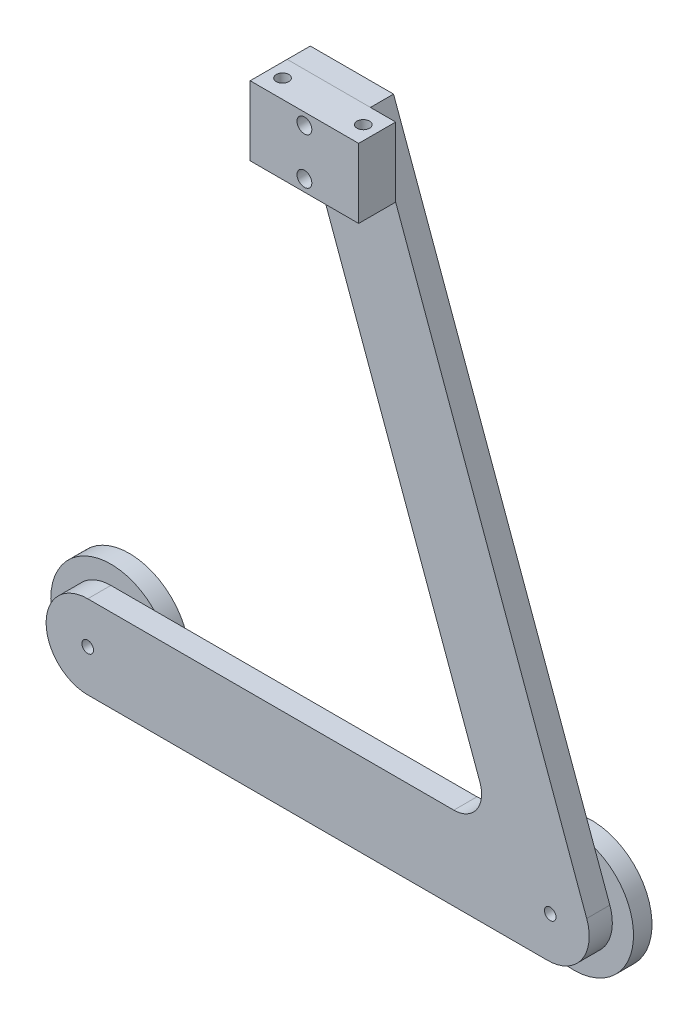
SolidWorks part; units mm, degrees
material "ﾊﾞﾙｻ"
ref_plane "正面" through (0, 0, 0) normal (0, 0, 1) x (1, 0, 0)
ref_plane "平面" through (0, 0, 0) normal (0, 1, 0) x (1, 0, 0)
ref_plane "右側面" through (0, 0, 0) normal (1, 0, 0) x (0, 0, -1)
sketch "ｽｹｯﾁ1" plane through (0, 0, 0) normal (0, 0, 1) x (1, 0, 0)
  line L0 (-44.6071, 122.557) -> (-2.9307, 8.0521)
  line L1 (-8.5689, 0) -> (-87.7243, 0)
  line L3 (-87.7243, -18) -> (11.6981, -18)
  line L4 (20.1554, -5.9218) -> (-26.6071, 122.557)
  line L5 (-26.6071, 122.557) -> (-44.6071, 122.557)
  line L6 (-87.7243, -9) -> (12.2757, -9) construction
  line L7 (12.2757, -9) -> (-35.6071, 122.557) construction
  arc A0 (11.6981, -18) -> (20.1554, -5.9218) centre (11.6981, -9) ccw
  arc A1 (-96.7243, -9) -> (-87.7243, -18) centre (-87.7243, -9) ccw
  arc A2 (-87.7243, 0) -> (-96.7243, -9) centre (-87.7243, -9) ccw
  circle A3 centre (12.2757, -9) radius 1.25
  circle A4 centre (-87.7243, -9) radius 1.25
  arc A5 (-2.9307, 8.0521) -> (-8.5689, 0) centre (-8.5689, 6) cw
  point P14 (-87.7243, -18)
  point P17 (-87.7243, 0)
  point P20 (0, 0)
  dimension "D1" = 6
  dimension "D6" = 2.5
  dimension "D2" = 140
  dimension "D3" = 100
  dimension "D4" = 18
  dimension "D5" = 18
  dimension "D7" = 70
extrude "ﾎﾞｽ - 押し出し1" add sketch "ｽｹｯﾁ1" along normal blind 5
sketch "ｽｹｯﾁ2" plane through (0, 0, 5) normal (0, 0, 1) x (1, 0, 0)
  line L0 (20.1554, -5.9218) -> (-26.6071, 122.557) construction
  line L1 (-44.6071, 122.557) -> (-21.1475, 122.557)
  line L2 (-44.6071, 122.557) -> (-44.6071, 107.557)
  line L3 (-44.6071, 107.557) -> (-21.1475, 107.557)
  line L4 (-21.1475, 122.557) -> (-21.1475, 107.557)
  line L5 (-44.6071, 115.057) -> (-21.1475, 115.057) construction
  line L7 (-32.8773, 122.557) -> (-32.8773, 107.557) construction
  dimension "D1" = 15
extrude "ﾎﾞｽ - 押し出し2" add sketch "ｽｹｯﾁ2" along normal blind 8 separate body
sketch "ｽｹｯﾁ3" plane through (0, 0, 13) normal (0, 0, 1) x (1, 0, 0)
  line L0 (-44.6071, 115.057) -> (-21.1475, 115.057) construction
  line L1 (-44.6071, 122.557) -> (-44.6071, 107.557) construction
  line L2 (-21.1475, 107.557) -> (-21.1475, 122.557) construction
  line L4 (-21.1475, 122.557) -> (-44.6071, 122.557) construction
  line L5 (-32.8773, 122.557) -> (-32.8773, 115.057) construction
  circle A0 centre (-32.8773, 120.057) radius 1.6
  circle A1 centre (-32.8773, 110.057) radius 1.6
  dimension "D1" = 3.2
  dimension "D2" = 10
extrude "ｶｯﾄ - 押し出し1" cut sketch "ｽｹｯﾁ3" against normal through all
sketch "ｽｹｯﾁ4" plane through (0, 107.557, 0) normal (0, -1, 0) x (1, 0, 0)
  line L0 (-21.1475, 9) -> (-44.6071, 9) construction
  line L1 (-21.1475, 13) -> (-21.1475, 5) construction
  line L2 (-44.6071, 13) -> (-44.6071, 5) construction
  line L4 (-44.6071, 13) -> (-21.1475, 13) construction
  line L5 (-32.8773, 13) -> (-32.8773, 5) construction
  line L6 (-44.6071, 5) -> (-21.1475, 5) construction
  circle A0 centre (-24.1475, 9) radius 1.35
  circle A1 centre (-41.6071, 9) radius 1.35
  dimension "D1" = 2.7
  dimension "D2" = 3
extrude "ｶｯﾄ - 押し出し2" cut sketch "ｽｹｯﾁ4" against normal through all
sketch "ｽｹｯﾁ6" plane through (0, 0, 0) normal (0, 0, -1) x (-1, 0, 0)
  circle A0 centre (-12.2757, -9) radius 3
  circle A1 centre (87.7243, -9) radius 3
  circle A2 centre (87.7243, -9) radius 1.25 construction
  circle A3 centre (-12.2757, -9) radius 1.25 construction
  circle A4 centre (87.7243, -9) radius 1.25
  circle A5 centre (-12.2757, -9) radius 1.25
  dimension "D1" = 6
extrude "ﾎﾞｽ - 押し出し3" add sketch "ｽｹｯﾁ6" along normal blind 5 separate body
sketch "ｽｹｯﾁ7" plane through (0, 0, 0) normal (0, 0, -1) x (-1, 0, 0)
  circle A0 centre (87.7243, -9) radius 3 construction
  circle A1 centre (-12.2757, -9) radius 3 construction
  circle A2 centre (87.7243, -9) radius 3
  circle A3 centre (-12.2757, -9) radius 3
  circle A4 centre (-12.2757, -9) radius 13
  circle A5 centre (87.7243, -9) radius 13
  dimension "D1" = 26
extrude "ﾎﾞｽ - 押し出し4" add sketch "ｽｹｯﾁ7" along normal blind 4 separate body
